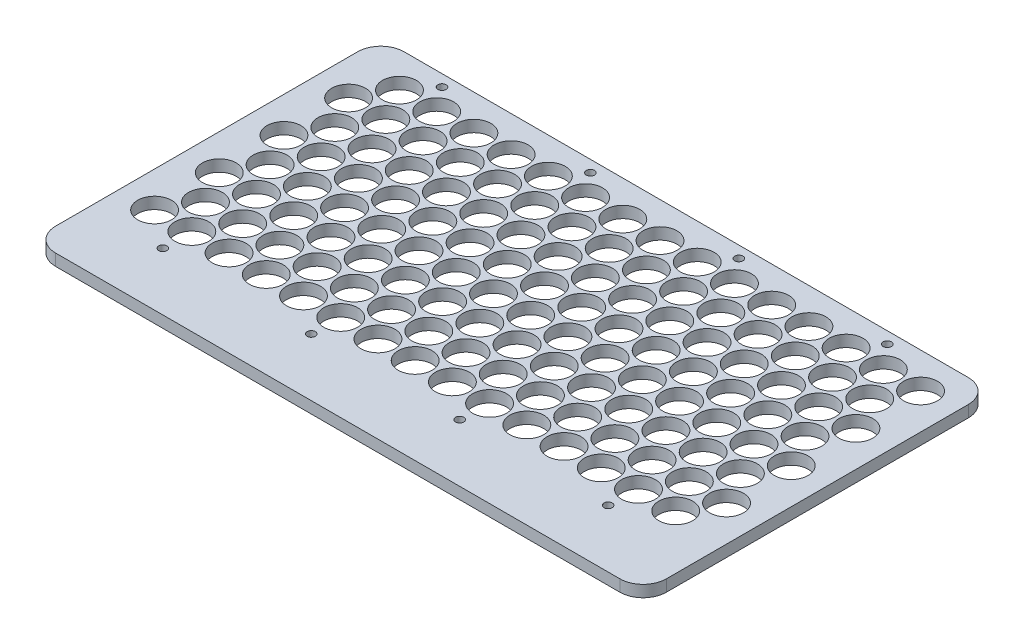
SolidWorks part; units mm, degrees
material "ABS"
ref_plane "X-Y Datum" through (0, 0, 0) normal (0, 0, 1) x (1, 0, 0)
ref_plane "X-Z Datum" through (0, 0, 0) normal (0, 1, 0) x (1, 0, 0)
ref_plane "Y-Z Datum" through (0, 0, 0) normal (1, 0, 0) x (0, 0, -1)
sketch "Sketch1" plane through (0, 0, 0) normal (0, 1, 0) x (1, 0, 0)
  line L0 (-9.25, 0) -> (-19.41, 0) construction
  line L2 (294.64, 132.7656) -> (294.64, 142.9256) construction
  line L3 (303.89, 123.5156) -> (314.05, 123.5156) construction
  line L4 (0, -9.25) -> (0, -47.35) construction
  line L5 (-19.41, -47.35) -> (314.05, -47.35)
  line L6 (-19.41, -47.35) -> (-19.41, 142.9256)
  line L7 (-19.41, 142.9256) -> (314.05, 142.9256)
  line L8 (314.05, -47.35) -> (314.05, 142.9256)
  circle A0 centre (0, 0) radius 9.25
  circle A1 centre (20.32, 0) radius 9.25
  circle A2 centre (40.64, 0) radius 9.25
  circle A3 centre (60.96, 0) radius 9.25
  circle A4 centre (81.28, 0) radius 9.25
  circle A5 centre (101.6, 0) radius 9.25
  circle A6 centre (121.92, 0) radius 9.25
  circle A7 centre (142.24, 0) radius 9.25
  circle A8 centre (162.56, 0) radius 9.25
  circle A9 centre (182.88, 0) radius 9.25
  circle A10 centre (203.2, 0) radius 9.25
  circle A11 centre (223.52, 0) radius 9.25
  circle A12 centre (243.84, 0) radius 9.25
  circle A13 centre (264.16, 0) radius 9.25
  circle A14 centre (284.48, 0) radius 9.25
  circle A15 centre (30.48, 17.5976) radius 9.25
  circle A16 centre (50.8, 17.5976) radius 9.25
  circle A17 centre (71.12, 17.5976) radius 9.25
  circle A18 centre (91.44, 17.5976) radius 9.25
  circle A19 centre (111.76, 17.5976) radius 9.25
  circle A20 centre (132.08, 17.5976) radius 9.25
  circle A21 centre (152.4, 17.5976) radius 9.25
  circle A22 centre (172.72, 17.5976) radius 9.25
  circle A23 centre (193.04, 17.5976) radius 9.25
  circle A24 centre (213.36, 17.5976) radius 9.25
  circle A25 centre (233.68, 17.5976) radius 9.25
  circle A26 centre (254, 17.5976) radius 9.25
  circle A27 centre (274.32, 17.5976) radius 9.25
  circle A28 centre (294.64, 17.5976) radius 9.25
  circle A29 centre (10.16, 17.5976) radius 9.25
  circle A30 centre (0, 35.306) radius 9.25
  circle A31 centre (20.32, 35.306) radius 9.25
  circle A32 centre (40.64, 35.306) radius 9.25
  circle A33 centre (60.96, 35.306) radius 9.25
  circle A34 centre (81.28, 35.306) radius 9.25
  circle A35 centre (101.6, 35.306) radius 9.25
  circle A36 centre (121.92, 35.306) radius 9.25
  circle A37 centre (142.24, 35.306) radius 9.25
  circle A38 centre (162.56, 35.306) radius 9.25
  circle A39 centre (182.88, 35.306) radius 9.25
  circle A40 centre (203.2, 35.306) radius 9.25
  circle A41 centre (223.52, 35.306) radius 9.25
  circle A42 centre (243.84, 35.306) radius 9.25
  circle A43 centre (264.16, 35.306) radius 9.25
  circle A44 centre (284.48, 35.306) radius 9.25
  circle A45 centre (30.48, 52.9036) radius 9.25
  circle A46 centre (50.8, 52.9036) radius 9.25
  circle A47 centre (71.12, 52.9036) radius 9.25
  circle A48 centre (91.44, 52.9036) radius 9.25
  circle A49 centre (111.76, 52.9036) radius 9.25
  circle A50 centre (132.08, 52.9036) radius 9.25
  circle A51 centre (152.4, 52.9036) radius 9.25
  circle A52 centre (172.72, 52.9036) radius 9.25
  circle A53 centre (193.04, 52.9036) radius 9.25
  circle A54 centre (213.36, 52.9036) radius 9.25
  circle A55 centre (233.68, 52.9036) radius 9.25
  circle A56 centre (254, 52.9036) radius 9.25
  circle A57 centre (274.32, 52.9036) radius 9.25
  circle A58 centre (294.64, 52.9036) radius 9.25
  circle A59 centre (10.16, 52.9036) radius 9.25
  circle A60 centre (0, 70.612) radius 9.25
  circle A61 centre (20.32, 70.612) radius 9.25
  circle A62 centre (40.64, 70.612) radius 9.25
  circle A63 centre (60.96, 70.612) radius 9.25
  circle A64 centre (81.28, 70.612) radius 9.25
  circle A65 centre (101.6, 70.612) radius 9.25
  circle A66 centre (121.92, 70.612) radius 9.25
  circle A67 centre (142.24, 70.612) radius 9.25
  circle A68 centre (162.56, 70.612) radius 9.25
  circle A69 centre (182.88, 70.612) radius 9.25
  circle A70 centre (203.2, 70.612) radius 9.25
  circle A71 centre (223.52, 70.612) radius 9.25
  circle A72 centre (243.84, 70.612) radius 9.25
  circle A73 centre (264.16, 70.612) radius 9.25
  circle A74 centre (284.48, 70.612) radius 9.25
  circle A75 centre (30.48, 88.2096) radius 9.25
  circle A76 centre (50.8, 88.2096) radius 9.25
  circle A77 centre (71.12, 88.2096) radius 9.25
  circle A78 centre (91.44, 88.2096) radius 9.25
  circle A79 centre (111.76, 88.2096) radius 9.25
  circle A80 centre (132.08, 88.2096) radius 9.25
  circle A81 centre (152.4, 88.2096) radius 9.25
  circle A82 centre (172.72, 88.2096) radius 9.25
  circle A83 centre (193.04, 88.2096) radius 9.25
  circle A84 centre (213.36, 88.2096) radius 9.25
  circle A85 centre (233.68, 88.2096) radius 9.25
  circle A86 centre (254, 88.2096) radius 9.25
  circle A87 centre (274.32, 88.2096) radius 9.25
  circle A88 centre (294.64, 88.2096) radius 9.25
  circle A89 centre (10.16, 88.2096) radius 9.25
  circle A90 centre (0, 105.918) radius 9.25
  circle A91 centre (20.32, 105.918) radius 9.25
  circle A92 centre (40.64, 105.918) radius 9.25
  circle A93 centre (60.96, 105.918) radius 9.25
  circle A94 centre (81.28, 105.918) radius 9.25
  circle A95 centre (101.6, 105.918) radius 9.25
  circle A96 centre (121.92, 105.918) radius 9.25
  circle A97 centre (142.24, 105.918) radius 9.25
  circle A98 centre (162.56, 105.918) radius 9.25
  circle A99 centre (182.88, 105.918) radius 9.25
  circle A100 centre (203.2, 105.918) radius 9.25
  circle A101 centre (223.52, 105.918) radius 9.25
  circle A102 centre (243.84, 105.918) radius 9.25
  circle A103 centre (264.16, 105.918) radius 9.25
  circle A104 centre (284.48, 105.918) radius 9.25
  circle A105 centre (30.48, 123.5156) radius 9.25
  circle A106 centre (50.8, 123.5156) radius 9.25
  circle A107 centre (71.12, 123.5156) radius 9.25
  circle A108 centre (91.44, 123.5156) radius 9.25
  circle A109 centre (111.76, 123.5156) radius 9.25
  circle A110 centre (132.08, 123.5156) radius 9.25
  circle A111 centre (152.4, 123.5156) radius 9.25
  circle A112 centre (172.72, 123.5156) radius 9.25
  circle A113 centre (193.04, 123.5156) radius 9.25
  circle A114 centre (213.36, 123.5156) radius 9.25
  circle A115 centre (233.68, 123.5156) radius 9.25
  circle A116 centre (254, 123.5156) radius 9.25
  circle A117 centre (274.32, 123.5156) radius 9.25
  circle A118 centre (294.64, 123.5156) radius 9.25
  circle A119 centre (10.16, 123.5156) radius 9.25
  dimension "D1" = 15
  dimension "D2" = 2
  dimension "D3" = 4
extrude "Boss-Extrude1" add sketch "Sketch1" along normal blind 6.35
fillet "Fillet1" radius 12.7 4 edges at (-19.41, 3.175, 47.35) (314.05, 3.175, 47.35) (314.05, 3.175, -142.9256) (-19.41, 3.175, -142.9256)
sketch "Sketch2" plane through (0, 6.35, 0) normal (0, 1, 0) x (1, 0, 0)
  line L0 (-6.71, 142.9256) -> (20.32, 142.9256) construction
  line L1 (301.35, 142.9256) -> (-6.71, 142.9256) construction
  line L2 (20.32, 142.9256) -> (20.32, 136.5756) construction
  line L3 (-6.71, 142.9256) -> (-6.71, -22.1744) construction
  line L4 (-6.71, 60.3756) -> (304.1925, 60.3756) construction
  circle A0 centre (20.32, 136.5756) radius 1.5274
  circle A1 centre (101.346, 136.5756) radius 1.5274
  circle A2 centre (182.372, 136.5756) radius 1.5274
  circle A3 centre (263.398, 136.5756) radius 1.5274
  circle A4 centre (263.398, -15.8244) radius 1.5274
  circle A5 centre (182.372, -15.8244) radius 1.5274
  circle A6 centre (101.346, -15.8244) radius 1.5274
  circle A7 centre (20.32, -15.8244) radius 1.5274
  point P7 (20.32, 136.5756)
  dimension "D1" = 4
hole_wizard "M4 Clearance Hole2" positions "Sketch5" profile "Sketch6" hole size "M4" standard "ANSI Metric" end condition through all
sketch "Sketch5" plane through (0, 6.35, 0) normal (0, 1, 0) x (1, 0, 0)
  point P0 (20.32, 136.5756)
  point P3 (101.346, 136.5756)
  point P6 (182.372, 136.5756)
  point P9 (263.398, 136.5756)
  point P12 (20.32, -15.8244)
  point P15 (101.346, -15.8244)
  point P18 (182.372, -15.8244)
  point P21 (263.398, -15.8244)
sketch "Sketch6" plane through (20.32, 6.35, -136.5756) normal (1, 0, 0) x (0, 0, 1)
  line L0 (0, 0) -> (0, 6.35)
  line L1 (0, 6.35) -> (2.25, 6.35)
  line L2 (2.25, 6.35) -> (2.25, 0)
  line L5 (2.25, 0) -> (0, 0)
  line L11 (0, -6.35) -> (0, 107.95) construction
  dimension "Thru Hole Dia." = 4.5
  dimension "Thru Hole Depth" = 6.35
